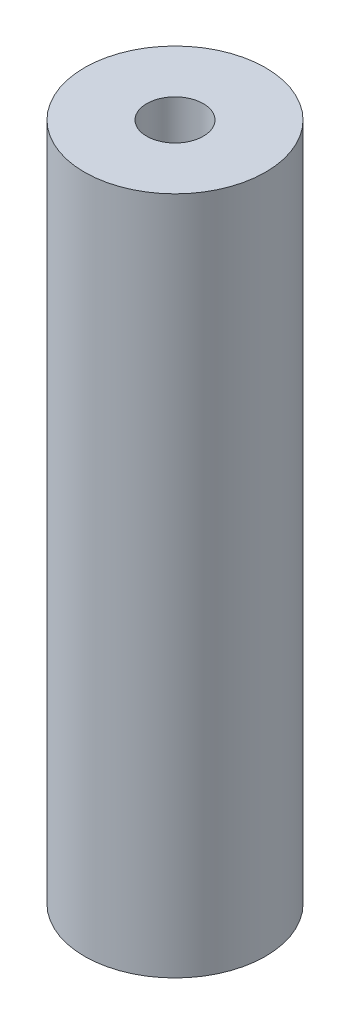
SolidWorks part; units mm, degrees
material "Сплав 2024"
ref_plane "Спереди" through (0, 0, 0) normal (0, 0, 1) x (1, 0, 0)
ref_plane "Сверху" through (0, 0, 0) normal (0, 1, 0) x (1, 0, 0)
ref_plane "Справа" through (0, 0, 0) normal (1, 0, 0) x (0, 0, -1)
sketch "Эскиз1" plane through (0, 0, 0) normal (0, 1, 0) x (1, 0, 0)
  circle A0 centre (0, 0) radius 4
  dimension "D1" = 8
extrude "Бобышка-Вытянуть1" add sketch "Эскиз1" along normal blind 30
hole_wizard "Отверстие обработанное метчиком M3x0.51" positions "Эскиз3" profile "Эскиз2" tap size "M3x0.5" standard "Ansi Metric" end condition through all
sketch "Эскиз3" plane through (0, 0, 0) normal (0, -1, 0) x (-1, 0, 0)
  point P0 (0, 0)
cosmetic thread "Отверстие резьбы1" parameters "D2"=3
sketch "Эскиз2" plane through (0, 0, 0) normal (1, 0, 0) x (0, 0, -1)
  line L0 (0, 0) -> (0, 30)
  line L1 (0, 30) -> (1.25, 30)
  line L2 (1.25, 30) -> (1.25, 0)
  line L5 (1.25, 0) -> (0, 0)
  line L11 (0, -6.35) -> (0, 107.95) construction
  dimension "Диаметр проходного сверла" = 2.5
  dimension "Глубина проходного сверла" = 30
hole_wizard "Отверстие обработанное метчиком M4x0.72" positions "Эскиз5" profile "Эскиз4" tap size "M4x0.7" standard "Ansi Metric"
sketch "Эскиз5" plane through (0, 30, 0) normal (0, 1, 0) x (1, 0, 0)
  point P0 (0, 0)
sketch "Эскиз4" plane through (0, 30, 0) normal (1, 0, 0) x (0, 0, 1)
  line L0 (0, 0) -> (0, 12.4914)
  line L1 (0, 12.4914) -> (1.65, 11.5)
  line L2 (1.65, 11.5) -> (1.65, 0)
  line L5 (1.65, 0) -> (0, 0)
  line L10 (0, 12.4914) -> (-1.65, 11.5) construction
  line L11 (0, -6.35) -> (0, 107.95) construction
  dimension "Диаметр сверла" = 3.3
  dimension "Глубина сверла" = 11.5
  dimension "Угол заточки сверла" = 118
